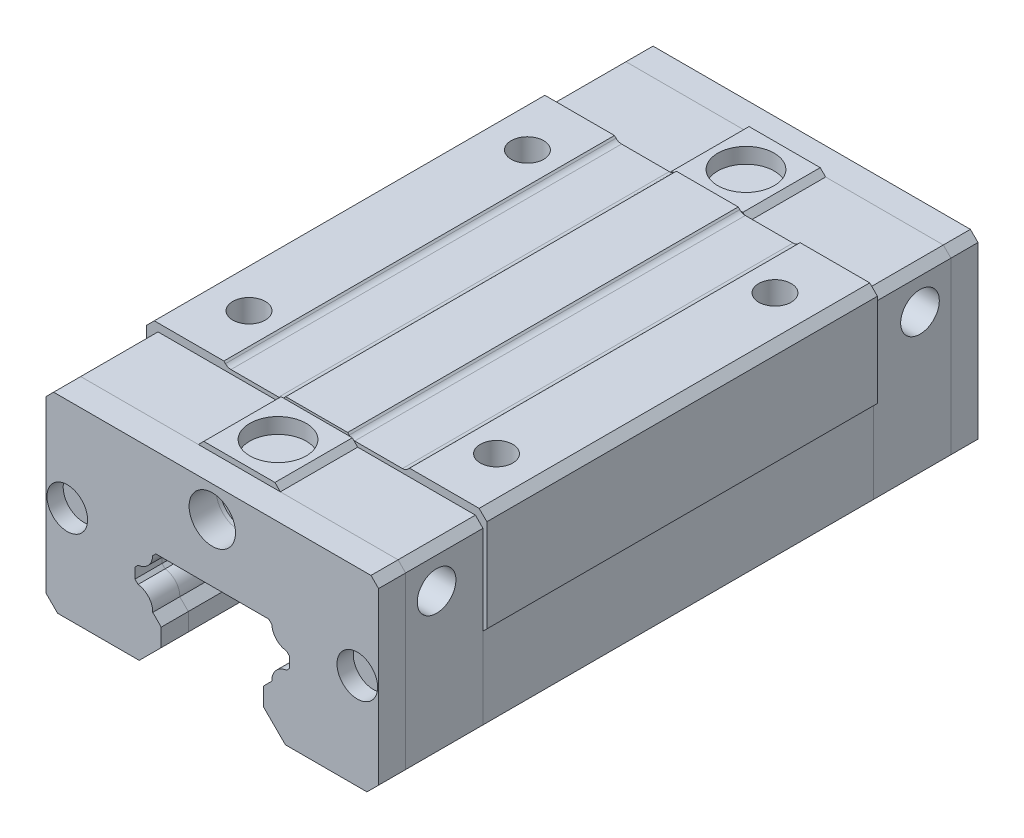
SolidWorks part; units mm, degrees
material "Stainless Steel (ferritic)"
ref_plane "Front Plane" through (0, 0, 0) normal (0, 0, 1) x (1, 0, 0)
ref_plane "Top Plane" through (0, 0, 0) normal (0, 1, 0) x (1, 0, 0)
ref_plane "Right Plane" through (0, 0, 0) normal (1, 0, 0) x (0, 0, -1)
sketch "Sketch1" plane through (0, 0, 0) normal (0, 0, 1) x (1, 0, 0)
  line L6 (-7.3, 3.5) -> (7.3, 3.5)
  line L7 (7.3, 3.5) -> (7.7, 3.1)
  line L8 (9.6, 1.075) -> (10, 0.675)
  line L9 (10, 0.675) -> (10, -0.675)
  line L10 (10, -0.675) -> (9.6, -1.075)
  line L11 (7.7, -3.25) -> (6.6, -4.35)
  line L12 (6.6, -4.35) -> (6.6, -6.65)
  line L13 (6.6, -6.65) -> (9.45, -9.5)
  line L14 (9.45, -9.5) -> (20, -9.5)
  line L15 (20, -9.5) -> (21.5, -8)
  line L16 (21.5, -8) -> (21.5, 2.5)
  line L17 (21.5, 2.5) -> (22, 3)
  line L18 (22, 3) -> (22, 15)
  line L19 (22, 15) -> (21, 16)
  line L20 (21, 16) -> (12, 16)
  line L21 (12, 16) -> (11.8, 15.8)
  line L22 (11.0859, 15.5) -> (4.9141, 15.5)
  line L23 (4.2, 15.8) -> (4, 16)
  line L24 (4, 16) -> (-4, 16)
  line L36 (-10, 0) -> (10, 0) construction
  line L37 (0, 0) -> (0, 16) construction
  line L38 (-4.2, 15.8) -> (-4, 16)
  line L39 (-11.0859, 15.5) -> (-4.9141, 15.5)
  line L40 (-12, 16) -> (-11.8, 15.8)
  line L41 (-21, 16) -> (-12, 16)
  line L47 (-9.45, -9.5) -> (-20, -9.5)
  line L48 (-6.6, -6.65) -> (-9.45, -9.5)
  line L49 (-6.6, -4.35) -> (-6.6, -6.65)
  line L50 (-7.7, -3.25) -> (-6.6, -4.35)
  line L51 (-10, -0.675) -> (-9.6, -1.075)
  line L52 (-10, 0.675) -> (-10, -0.675)
  line L53 (-9.6, 1.075) -> (-10, 0.675)
  line L54 (-7.3, 3.5) -> (-7.7, 3.1)
  line L55 (-22, 15) -> (-21, 16)
  line L56 (-21.5, -8) -> (-21.5, 7.5)
  line L57 (-20, -9.5) -> (-21.5, -8)
  line L58 (-22, 15) -> (-22, 8)
  line L59 (-22, 8) -> (-21.5, 7.5)
  arc A2 (7.7, 3.1) -> (9.6, 1.075) centre (9.828, 3.1928) ccw
  arc A3 (9.6, -1.075) -> (7.7, -3.25) centre (9.8292, -3.1926) ccw
  arc A4 (11.0859, 15.5) -> (11.8, 15.8) centre (11.0859, 16.5) ccw
  arc A5 (4.2, 15.8) -> (4.9141, 15.5) centre (4.9141, 16.5) ccw
  arc A6 (-4.2, 15.8) -> (-4.9141, 15.5) centre (-4.9141, 16.5) cw
  arc A7 (-11.0859, 15.5) -> (-11.8, 15.8) centre (-11.0859, 16.5) cw
  arc A8 (-9.6, -1.075) -> (-7.7, -3.25) centre (-9.8292, -3.1926) cw
  arc A9 (-7.7, 3.1) -> (-9.6, 1.075) centre (-9.828, 3.1928) cw
  point P0 (-8, 15.5)
  point P2 (6.6, -5.5)
  point P5 (8, 15.5)
  point P68 (0, 3.5)
  point P69 (-6.6, -5.5)
  dimension "D23" = 1
  dimension "D31" = 2.13
  dimension "D3" = 21.5
  dimension "D4" = 0.5
  dimension "D5" = 22
  dimension "D6" = 13
  dimension "D7" = 3.5
  dimension "D8" = 6.6
  dimension "D9" = 45
  dimension "D10" = 45
  dimension "D11" = 45
  dimension "D12" = 45
  dimension "D13" = 45
  dimension "D14" = 45
  dimension "D15" = 45
  dimension "D16" = 4
  dimension "D17" = 9
  dimension "D18" = 1
  dimension "D19" = 1.5
  dimension "D20" = 10
  dimension "D21" = 4
  dimension "D22" = 0.2
  dimension "D24" = 0.5
  dimension "D25" = 0.2
  dimension "D26" = 8
  dimension "D27" = 13
  dimension "D28" = 9.5
  dimension "D29" = 1.35
  dimension "D30" = 2.85
  dimension "D32" = 0.4
  dimension "D33" = 0.4
  dimension "D34" = 7.3
  dimension "D35" = 45
  dimension "D36" = 45
  dimension "D37" = 45
  dimension "D38" = 1.1
  dimension "D39" = 12
  dimension "D40" = 7
  dimension "D41" = 45
  dimension "D42" = 16
extrude "BASE" add sketch "Sketch1" along normal mid plane 50.5
hole_wizard "M5x0.8 Tapped Hole1" positions "Sketch2" profile "Sketch3" tap size "M5x0.8" standard "ANSI Metric"
sketch "Sketch2" plane through (0, 16, 0) normal (0, 1, 0) x (1, 0, 0)
  line L0 (-22, -25.25) -> (-22, 25.25) construction
  line L1 (-12, 25.25) -> (-21, 25.25) construction
  point P0 (-16, 18)
  dimension "D1" = 6
  dimension "D2" = 7.25
  dimension "D3" = 18
  dimension "D4" = 16
sketch "Sketch3" plane through (-16, 16, -18) normal (1, 0, 0) x (0, 0, 1)
  line L0 (0, 0) -> (0, 7.2618)
  line L1 (0, 7.2618) -> (2.1, 6)
  line L2 (2.1, 6) -> (2.1, 0)
  line L5 (2.1, 0) -> (0, 0)
  line L10 (0, 7.2618) -> (-2.1, 6) construction
  line L11 (0, -6.35) -> (0, 107.95) construction
  dimension "Tap Drill Dia." = 4.2
  dimension "Tap Drill Depth" = 6
  dimension "Drill Angle" = 118
cosmetic thread "Hole Thread1" parameters "D1"=6, "D2"=5
mirror "HM" about plane through (0, 0, 0) normal (1, 0, 0) of "M5x0.8 Tapped Hole1"
mirror "VM" about plane through (0, 0, 0) normal (0, 0, 1) of "HM", "M5x0.8 Tapped Hole1"
sketch "Sketch4" plane through (0, 0, 25.25) normal (0, 0, 1) x (1, 0, 0)
  line L0 (-21.5, 14.0165) -> (-20.5165, 15)
  line L1 (-20.5165, 15) -> (-5.3, 15)
  line L2 (-5.3, 15) -> (-4.6, 15.7)
  line L3 (-4.6, 15.7) -> (4.6, 15.7)
  line L4 (4.6, 15.7) -> (5.3, 15)
  line L5 (5.3, 15) -> (20.5165, 15)
  line L6 (20.5165, 15) -> (21.5, 14.0165)
  line L7 (0, 3.5) -> (0, 15.7) construction
  line L9 (-12, 16) -> (-21, 16) construction
  line L10 (4, 16) -> (-4, 16) construction
  line L36 (-22, 15) -> (-22, 8)
  line L37 (-22, 8) -> (-21.5, 7.5)
  line L38 (-21.5, 7.5) -> (-21.5, -8)
  line L39 (-21.5, -8) -> (-20, -9.5)
  line L40 (-20, -9.5) -> (-9.45, -9.5)
  line L41 (-9.45, -9.5) -> (-6.6, -6.65)
  line L42 (-6.6, -6.65) -> (-6.6, -4.35)
  line L43 (-6.6, -4.35) -> (-7.7, -3.25)
  line L44 (-9.6, -1.075) -> (-10, -0.675)
  line L45 (-10, -0.675) -> (-10, 0.675)
  line L46 (-10, 0.675) -> (-9.6, 1.075)
  line L47 (-7.7, 3.1) -> (-7.3, 3.5)
  line L48 (-7.3, 3.5) -> (7.3, 3.5)
  line L49 (7.3, 3.5) -> (7.7, 3.1)
  line L50 (9.6, 1.075) -> (10, 0.675)
  line L51 (10, 0.675) -> (10, -0.675)
  line L52 (10, -0.675) -> (9.6, -1.075)
  line L53 (7.7, -3.25) -> (6.6, -4.35)
  line L54 (6.6, -4.35) -> (6.6, -6.65)
  line L55 (6.6, -6.65) -> (9.45, -9.5)
  line L56 (9.45, -9.5) -> (20, -9.5)
  line L57 (20, -9.5) -> (21.5, -8)
  line L58 (21.5, -8) -> (21.5, 2.5)
  line L59 (21.5, 2.5) -> (22, 3)
  line L60 (22, 3) -> (22, 15)
  line L61 (22, 15) -> (21, 16)
  line L62 (21, 16) -> (12, 16)
  line L63 (12, 16) -> (11.8, 15.8)
  line L64 (11.0859, 15.5) -> (4.9141, 15.5)
  line L65 (4.2, 15.8) -> (4, 16)
  line L66 (4, 16) -> (-4, 16)
  line L67 (-4, 16) -> (-4.2, 15.8)
  line L68 (-4.9141, 15.5) -> (-11.0859, 15.5)
  line L69 (-11.8, 15.8) -> (-12, 16)
  line L70 (-12, 16) -> (-21, 16)
  line L71 (-21, 16) -> (-22, 15)
  line L74 (-21.5, 14.0165) -> (-21.5, -8)
  line L75 (-21.5, -8) -> (-20, -9.5)
  line L76 (-20, -9.5) -> (-9.45, -9.5)
  line L77 (-9.45, -9.5) -> (-6.6, -6.65)
  line L78 (-6.6, -6.65) -> (-6.6, -4.35)
  line L79 (-6.6, -4.35) -> (-7.7, -3.25)
  line L80 (-9.6, -1.075) -> (-10, -0.675)
  line L81 (-10, -0.675) -> (-10, 0.675)
  line L82 (-10, 0.675) -> (-9.6, 1.075)
  line L83 (-7.7, 3.1) -> (-7.3, 3.5)
  line L84 (-7.3, 3.5) -> (7.3, 3.5)
  line L85 (7.3, 3.5) -> (7.7, 3.1)
  line L86 (9.6, 1.075) -> (10, 0.675)
  line L87 (10, 0.675) -> (10, -0.675)
  line L88 (10, -0.675) -> (9.6, -1.075)
  line L89 (7.7, -3.25) -> (6.6, -4.35)
  line L90 (6.6, -4.35) -> (6.6, -6.65)
  line L91 (6.6, -6.65) -> (9.45, -9.5)
  line L92 (9.45, -9.5) -> (20, -9.5)
  line L93 (20, -9.5) -> (21.5, -8)
  line L94 (21.5, -8) -> (21.5, 14.0165)
  arc A8 (-7.7, -3.25) -> (-9.6, -1.075) centre (-9.8292, -3.1926) ccw
  arc A9 (-9.6, 1.075) -> (-7.7, 3.1) centre (-9.828, 3.1928) ccw
  arc A10 (7.7, 3.1) -> (9.6, 1.075) centre (9.828, 3.1928) ccw
  arc A11 (9.6, -1.075) -> (7.7, -3.25) centre (9.8292, -3.1926) ccw
  arc A12 (11.0859, 15.5) -> (11.8, 15.8) centre (11.0859, 16.5) ccw
  arc A13 (4.2, 15.8) -> (4.9141, 15.5) centre (4.9141, 16.5) ccw
  arc A14 (-4.9141, 15.5) -> (-4.2, 15.8) centre (-4.9141, 16.5) ccw
  arc A15 (-11.8, 15.8) -> (-11.0859, 15.5) centre (-11.0859, 16.5) ccw
  arc A16 (-7.7, -3.25) -> (-9.6, -1.075) centre (-9.8292, -3.1926) ccw
  arc A17 (-9.6, 1.075) -> (-7.7, 3.1) centre (-9.828, 3.1928) ccw
  arc A18 (7.7, 3.1) -> (9.6, 1.075) centre (9.828, 3.1928) ccw
  arc A19 (9.6, -1.075) -> (7.7, -3.25) centre (9.8292, -3.1926) ccw
  dimension "D2" = 1
  dimension "D3" = 9.2
  dimension "D4" = 45
  dimension "D5" = 0.3
  dimension "D6" = 45
  dimension "D1" = 0
extrude "GREEN BODY" add sketch "Sketch4" along normal blind 10 separate body
sketch "Sketch5" plane through (0, 15.7, 0) normal (0, 1, 0) x (1, 0, 0)
  line L0 (-4.6, -25.25) -> (4.6, -35.25) construction
  circle A0 centre (0, -30.25) radius 3.65
  dimension "D1" = 7.3
extrude "TOP HOLE GB" cut sketch "Sketch5" against normal blind 2
sketch "Sketch6" plane through (-21.5, 0, 0) normal (-1, 0, 0) x (0, 0, 1)
  line L0 (35.25, 14.0165) -> (35.25, -8) construction
  line L1 (35.25, 15) -> (25.25, 15) construction
  circle A0 centre (31.25, 10) radius 2.5
  dimension "D1" = 4
  dimension "D3" = 5
  dimension "D2" = 5
extrude "SIDE HOLE GB" cut sketch "Sketch6" against normal blind 6.7
mirror "SHGB HM" about plane through (0, 0, 0) normal (1, 0, 0) of "SIDE HOLE GB"
sketch "Sketch7" plane through (0, 0, -25.25) normal (0, 0, -1) x (-1, 0, 0)
  line L28 (-20.5165, 15) -> (-21.5, 14.0165)
  line L29 (-5.3, 15) -> (-20.5165, 15)
  line L30 (-4.6, 15.7) -> (-5.3, 15)
  line L31 (4.6, 15.7) -> (-4.6, 15.7)
  line L32 (5.3, 15) -> (4.6, 15.7)
  line L33 (20.5165, 15) -> (5.3, 15)
  line L34 (21.5, 14.0165) -> (20.5165, 15)
  line L35 (21.5, -8) -> (21.5, 14.0165)
  line L36 (20, -9.5) -> (21.5, -8)
  line L37 (9.45, -9.5) -> (20, -9.5)
  line L38 (6.6, -6.65) -> (9.45, -9.5)
  line L39 (6.6, -4.35) -> (6.6, -6.65)
  line L40 (7.7, -3.25) -> (6.6, -4.35)
  line L41 (10, -0.675) -> (9.6, -1.075)
  line L42 (10, 0.675) -> (10, -0.675)
  line L43 (9.6, 1.075) -> (10, 0.675)
  line L44 (7.3, 3.5) -> (7.7, 3.1)
  line L45 (-7.3, 3.5) -> (7.3, 3.5)
  line L46 (-7.7, 3.1) -> (-7.3, 3.5)
  line L47 (-10, 0.675) -> (-9.6, 1.075)
  line L48 (-10, -0.675) -> (-10, 0.675)
  line L49 (-9.6, -1.075) -> (-10, -0.675)
  line L50 (-6.6, -4.35) -> (-7.7, -3.25)
  line L51 (-6.6, -6.65) -> (-6.6, -4.35)
  line L52 (-9.45, -9.5) -> (-6.6, -6.65)
  line L53 (-20, -9.5) -> (-9.45, -9.5)
  line L54 (-21.5, -8) -> (-20, -9.5)
  line L55 (-21.5, 14.0165) -> (-21.5, -8)
  line L56 (-20.5165, 15) -> (-21.5, 14.0165)
  line L57 (-5.3, 15) -> (-20.5165, 15)
  line L58 (-4.6, 15.7) -> (-5.3, 15)
  line L59 (4.6, 15.7) -> (-4.6, 15.7)
  line L60 (5.3, 15) -> (4.6, 15.7)
  line L61 (20.5165, 15) -> (5.3, 15)
  line L62 (21.5, 14.0165) -> (20.5165, 15)
  line L63 (21.5, -8) -> (21.5, 14.0165)
  line L64 (20, -9.5) -> (21.5, -8)
  line L65 (9.45, -9.5) -> (20, -9.5)
  line L66 (6.6, -6.65) -> (9.45, -9.5)
  line L67 (6.6, -4.35) -> (6.6, -6.65)
  line L68 (7.7, -3.25) -> (6.6, -4.35)
  line L69 (10, -0.675) -> (9.6, -1.075)
  line L70 (10, 0.675) -> (10, -0.675)
  line L71 (9.6, 1.075) -> (10, 0.675)
  line L72 (7.3, 3.5) -> (7.7, 3.1)
  line L73 (-7.3, 3.5) -> (7.3, 3.5)
  line L74 (-7.7, 3.1) -> (-7.3, 3.5)
  line L75 (-10, 0.675) -> (-9.6, 1.075)
  line L76 (-10, -0.675) -> (-10, 0.675)
  line L77 (-9.6, -1.075) -> (-10, -0.675)
  line L78 (-6.6, -4.35) -> (-7.7, -3.25)
  line L79 (-6.6, -6.65) -> (-6.6, -4.35)
  line L80 (-9.45, -9.5) -> (-6.6, -6.65)
  line L81 (-20, -9.5) -> (-9.45, -9.5)
  line L82 (-21.5, -8) -> (-20, -9.5)
  line L83 (-21.5, 14.0165) -> (-21.5, -8)
  arc A4 (9.6, -1.075) -> (7.7, -3.25) centre (9.8292, -3.1926) ccw
  arc A5 (7.7, 3.1) -> (9.6, 1.075) centre (9.828, 3.1928) ccw
  arc A6 (-9.6, 1.075) -> (-7.7, 3.1) centre (-9.828, 3.1928) ccw
  arc A7 (-7.7, -3.25) -> (-9.6, -1.075) centre (-9.8292, -3.1926) ccw
  arc A8 (9.6, -1.075) -> (7.7, -3.25) centre (9.8292, -3.1926) ccw
  arc A9 (7.7, 3.1) -> (9.6, 1.075) centre (9.828, 3.1928) ccw
  arc A10 (-9.6, 1.075) -> (-7.7, 3.1) centre (-9.828, 3.1928) ccw
  arc A11 (-7.7, -3.25) -> (-9.6, -1.075) centre (-9.8292, -3.1926) ccw
  dimension "D1" = 0
extrude "GREEN BODY VM" add sketch "Sketch7" along normal blind 10 separate body
mirror "GB FEATURES VM" about plane through (0, 0, 0) normal (0, 0, 1) of "SIDE HOLE GB", "SHGB HM", "TOP HOLE GB"
sketch "Sketch8" plane through (0, 0, 35.25) normal (0, 0, 1) x (1, 0, 0)
  line L0 (-20.5165, 15) -> (20.5165, 15)
  line L28 (-21.5, 14.0165) -> (-21.5, -8)
  line L29 (-21.5, -8) -> (-20, -9.5)
  line L30 (-20, -9.5) -> (-9.45, -9.5)
  line L31 (-9.45, -9.5) -> (-6.6, -6.65)
  line L32 (-6.6, -6.65) -> (-6.6, -4.35)
  line L33 (-6.6, -4.35) -> (-7.7, -3.25)
  line L34 (-9.6, -1.075) -> (-10, -0.675)
  line L35 (-10, -0.675) -> (-10, 0.675)
  line L36 (-10, 0.675) -> (-9.6, 1.075)
  line L37 (-7.7, 3.1) -> (-7.3, 3.5)
  line L38 (-7.3, 3.5) -> (7.3, 3.5)
  line L39 (7.3, 3.5) -> (7.7, 3.1)
  line L40 (9.6, 1.075) -> (10, 0.675)
  line L41 (10, 0.675) -> (10, -0.675)
  line L42 (10, -0.675) -> (9.6, -1.075)
  line L43 (7.7, -3.25) -> (6.6, -4.35)
  line L44 (6.6, -4.35) -> (6.6, -6.65)
  line L45 (6.6, -6.65) -> (9.45, -9.5)
  line L46 (9.45, -9.5) -> (20, -9.5)
  line L47 (20, -9.5) -> (21.5, -8)
  line L48 (21.5, -8) -> (21.5, 14.0165)
  line L49 (21.5, 14.0165) -> (20.5165, 15)
  line L50 (20.5165, 15) -> (5.3, 15)
  line L51 (5.3, 15) -> (4.6, 15.7)
  line L52 (4.6, 15.7) -> (-4.6, 15.7)
  line L53 (-4.6, 15.7) -> (-5.3, 15)
  line L54 (-5.3, 15) -> (-20.5165, 15)
  line L55 (-20.5165, 15) -> (-21.5, 14.0165)
  line L56 (-21.5, 14.0165) -> (-21.5, -8)
  line L57 (-21.5, -8) -> (-20, -9.5)
  line L58 (-20, -9.5) -> (-9.45, -9.5)
  line L59 (-9.45, -9.5) -> (-6.6, -6.65)
  line L60 (-6.6, -6.65) -> (-6.6, -4.35)
  line L61 (-6.6, -4.35) -> (-7.7, -3.25)
  line L62 (-9.6, -1.075) -> (-10, -0.675)
  line L63 (-10, -0.675) -> (-10, 0.675)
  line L64 (-10, 0.675) -> (-9.6, 1.075)
  line L65 (-7.7, 3.1) -> (-7.3, 3.5)
  line L66 (-7.3, 3.5) -> (7.3, 3.5)
  line L67 (7.3, 3.5) -> (7.7, 3.1)
  line L68 (9.6, 1.075) -> (10, 0.675)
  line L69 (10, 0.675) -> (10, -0.675)
  line L70 (10, -0.675) -> (9.6, -1.075)
  line L71 (7.7, -3.25) -> (6.6, -4.35)
  line L72 (6.6, -4.35) -> (6.6, -6.65)
  line L73 (6.6, -6.65) -> (9.45, -9.5)
  line L74 (9.45, -9.5) -> (20, -9.5)
  line L75 (20, -9.5) -> (21.5, -8)
  line L76 (21.5, -8) -> (21.5, 14.0165)
  line L77 (21.5, 14.0165) -> (20.5165, 15)
  line L83 (-20.5165, 15) -> (-21.5, 14.0165)
  arc A4 (-7.7, -3.25) -> (-9.6, -1.075) centre (-9.8292, -3.1926) ccw
  arc A5 (-9.6, 1.075) -> (-7.7, 3.1) centre (-9.828, 3.1928) ccw
  arc A6 (7.7, 3.1) -> (9.6, 1.075) centre (9.828, 3.1928) ccw
  arc A7 (9.6, -1.075) -> (7.7, -3.25) centre (9.8292, -3.1926) ccw
  arc A8 (-7.7, -3.25) -> (-9.6, -1.075) centre (-9.8292, -3.1926) ccw
  arc A9 (-9.6, 1.075) -> (-7.7, 3.1) centre (-9.828, 3.1928) ccw
  arc A10 (7.7, 3.1) -> (9.6, 1.075) centre (9.828, 3.1928) ccw
  arc A11 (9.6, -1.075) -> (7.7, -3.25) centre (9.8292, -3.1926) ccw
  dimension "D1" = 0
extrude "RED BODY" add sketch "Sketch8" along normal blind 3.5 separate body
sketch "Sketch9" plane through (0, 0, 38.75) normal (0, 0, 1) x (1, 0, 0)
  line L0 (-20, -9.5) -> (-9.45, -9.5) construction
  line L1 (-21.5, 14.0165) -> (-21.5, -8) construction
  circle A0 centre (-18.75, 2.9) radius 2.625
  dimension "D3" = 5.25
  dimension "D1" = 12.4
  dimension "D2" = 2.75
extrude "RB HOLE" cut sketch "Sketch9" against normal blind 2.1
mirror "RBH HM" about plane through (0, 0, 0) normal (1, 0, 0) of "RB HOLE"
mirror "RB AND HOLES VM" about plane through (0, 0, 0) normal (0, 0, 1) of bodies 117
sketch "Sketch10" plane through (0, 0, 38.75) normal (0, 0, 1) x (1, 0, 0)
  line L0 (0, 15) -> (0, 11) construction
  line L2 (20.5165, 15) -> (-20.5165, 15) construction
  circle A0 centre (0, 11) radius 3
  dimension "D2" = 6
  dimension "D1" = 4
extrude "Cut-Extrude1" cut sketch "Sketch10" against normal blind 4
